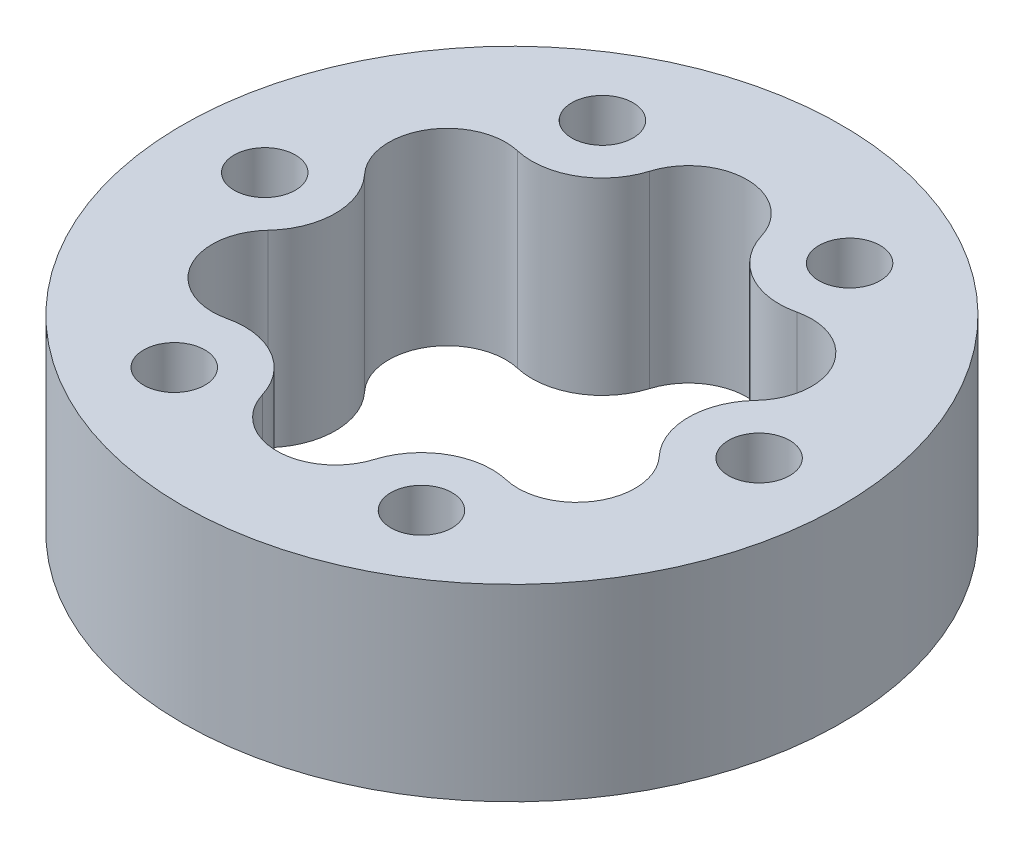
SolidWorks part; units mm, degrees
material "ABS"
ref_plane "前视基准面" through (0, 0, 0) normal (0, 0, 1) x (1, 0, 0)
ref_plane "上视基准面" through (0, 0, 0) normal (0, 1, 0) x (1, 0, 0)
ref_plane "右视基准面" through (0, 0, 0) normal (1, 0, 0) x (0, 0, -1)
sketch "草图1" plane through (0, 0, 0) normal (0, 1, 0) x (1, 0, 0)
  line L0 (0, 25) -> (0, 0) construction
  line L1 (0, 0) -> (10.5, 18.1865) construction
  circle A0 centre (0, 0) radius 28
  circle A1 centre (0, 0) radius 25 construction
  circle A2 centre (0, 25) radius 1.25 construction
  circle A3 centre (21.6506, 12.5) radius 1.25 construction
  circle A4 centre (21.6506, -12.5) radius 1.25 construction
  circle A5 centre (0, -25) radius 1.25 construction
  circle A6 centre (-21.6506, -12.5) radius 1.25 construction
  circle A7 centre (-21.6506, 12.5) radius 1.25 construction
  circle A8 centre (0, 0) radius 15 construction
  circle A9 centre (0, 15) radius 4 construction
  circle A10 centre (12.9904, -7.5) radius 4 construction
  circle A11 centre (-12.9904, -7.5) radius 4 construction
  circle A12 centre (0, 0) radius 21 construction
  circle A13 centre (10.5, 18.1865) radius 2.6
  circle A14 centre (21, 0) radius 2.6
  circle A15 centre (10.5, -18.1865) radius 2.6
  circle A16 centre (-10.5, -18.1865) radius 2.6
  circle A17 centre (-21, 0) radius 2.6
  circle A18 centre (-10.5, 18.1865) radius 2.6
  dimension "D1" = 2.5
  dimension "D2" = 50
  dimension "D3" = 56
  dimension "D5" = 30
  dimension "D6" = 8
  dimension "D9" = 5.2
  dimension "D10" = 42
  dimension "D8" = 30
  dimension "D4" = 6
  dimension "D7" = 3
  dimension "D11" = 6
extrude "凸台-拉伸1" add sketch "草图1" along normal blind 16
sketch "草图4" plane through (0, 16, 0) normal (0, 1, 0) x (1, 0, 0)
  circle A0 centre (0, 0) radius 15 construction
  circle A1 centre (0, 15) radius 4 construction
  circle A2 centre (12.9904, 7.5) radius 4 construction
  circle A3 centre (12.9904, -7.5) radius 4 construction
  circle A4 centre (0, -15) radius 4 construction
  circle A5 centre (-12.9904, -7.5) radius 4 construction
  circle A6 centre (-12.9904, 7.5) radius 4 construction
  arc A7 (4.7586, 16.4441) -> (11.8617, 12.3431) centre (10.5, 18.1865) ccw
  arc A8 (-4.7586, 16.4441) -> (4.7586, 16.4441) centre (0, 15) cw
  arc A9 (11.8617, 12.3431) -> (16.6203, 4.101) centre (12.9904, 7.5) cw
  arc A10 (16.6203, 4.101) -> (16.6203, -4.101) centre (21, 0) ccw
  arc A11 (16.6203, -4.101) -> (11.8617, -12.3431) centre (12.9904, -7.5) cw
  arc A12 (11.8617, -12.3431) -> (4.7586, -16.4441) centre (10.5, -18.1865) ccw
  arc A13 (4.7586, -16.4441) -> (-4.7586, -16.4441) centre (0, -15) cw
  arc A14 (-4.7586, -16.4441) -> (-11.8617, -12.3431) centre (-10.5, -18.1865) ccw
  arc A15 (-11.8617, -12.3431) -> (-16.6203, -4.101) centre (-12.9904, -7.5) cw
  arc A16 (-16.6203, -4.101) -> (-16.6203, 4.101) centre (-21, 0) ccw
  arc A17 (-16.6203, 4.101) -> (-11.8617, 12.3431) centre (-12.9904, 7.5) cw
  arc A18 (-11.8617, 12.3431) -> (-4.7586, 16.4441) centre (-10.5, 18.1865) ccw
  dimension "D1" = 30
  dimension "D2" = 8
  dimension "D4" = 6
  dimension "D3" = 6
  dimension "D5" = 6
extrude "切除-拉伸2" cut sketch "草图4" against normal through all and the other way through all
move or copy body "实体-移动/复制1" [suppressed] bodies to move or copy 109
